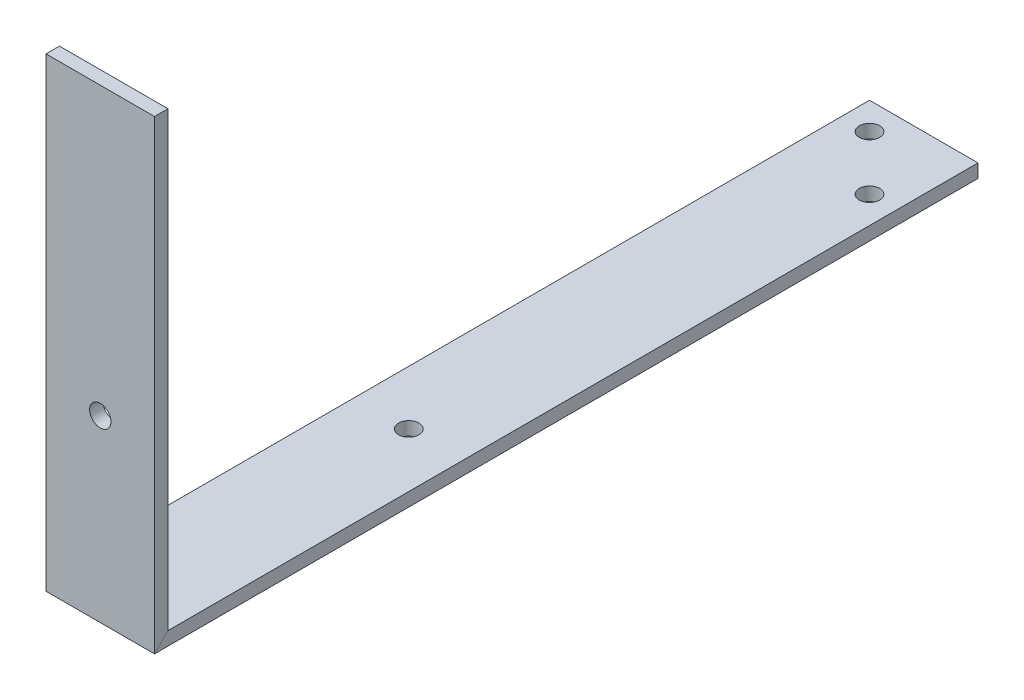
SolidWorks part; units mm, degrees
ref_plane "Alzado" through (0, 0, 0) normal (0, 0, 1) x (1, 0, 0)
ref_plane "Planta" through (0, 0, 0) normal (0, 1, 0) x (1, 0, 0)
ref_plane "Vista lateral" through (0, 0, 0) normal (1, 0, 0) x (0, 0, -1)
sketch "Croquis2" plane through (0, 0, 0) normal (0, 1, 0) x (1, 0, 0)
  line L1 (-25.4, 3.155) -> (25.4, 3.155)
  line L2 (-25.4, 3.155) -> (-25.4, -3.155)
  line L3 (-25.4, -3.155) -> (25.4, -3.155)
  line L4 (25.4, 3.155) -> (25.4, -3.155)
  line L5 (-25.4, 3.155) -> (25.4, -3.155) construction
  line L6 (-25.4, -3.155) -> (25.4, 3.155) construction
  line L7 (184.6, 3.155) -> (235.4, 3.155)
  line L8 (184.6, 3.155) -> (184.6, -3.155)
  line L9 (184.6, -3.155) -> (235.4, -3.155)
  line L10 (235.4, 3.155) -> (235.4, -3.155)
  line L11 (184.6, 3.155) -> (235.4, -3.155) construction
  line L12 (184.6, -3.155) -> (235.4, 3.155) construction
  point P0 (0, 0)
  point P6 (210, 0)
  dimension "D1" = 50.8
  dimension "D2" = 6.31
  dimension "D3" = 210
  dimension "D4" = 50.8
  dimension "D5" = 6.31
sketch3d "Croquis3D1"
  line L0 (0, 0, 0) -> (0, -567.24, 0)
  line L1 (0, -567.24, 0) -> (0, -567.24, 336.2)
  line L2 (0, -567.24, 336.2) -> (1786.7, -567.24, 336.2)
  line L3 (1786.7, -567.24, 336.2) -> (1786.7, -567.24, 693.16)
  line L4 (-25.4, 0, 0) -> (-25.4, -383.9185, 0) construction
  line L5 (-25.4, 0, -3.155) -> (-25.4, 0, 3.155) construction
  line L6 (-25.4, -383.9185, 0) -> (-25.4, -383.9185, 653.2834) construction
  line L7 (1786.7, -567.24, 693.16) -> (1786.7, -436.23, 693.16)
  line L8 (1786.7, -436.23, 693.16) -> (1786.7, -436.23, 1487.1629)
  dimension "D1" = 567.24
  dimension "D2" = 336.2
  dimension "D3" = 1786.7
  dimension "D4" = 356.96
  dimension "D5" = 131.01
  dimension "D6" = 794.0029
sweep "Barrer1" add profiles "Croquis2" path "Croquis3D1"
sketch "Croquis3" plane through (0, 0, -3.155) normal (0, 0, -1) x (-1, 0, 0)
  line L0 (-235.4, 0) -> (-235.4, -6.31)
  line L1 (-235.4, 0) -> (-235.4, -570.395) construction
  line L2 (-235.4, -6.31) -> (-184.6, -6.31)
  line L3 (-184.6, 0) -> (-184.6, -570.395) construction
  line L4 (-184.6, -6.31) -> (-184.6, 0)
  line L5 (-184.6, 0) -> (-235.4, 0)
  line L7 (-25.4, 0) -> (-25.4, -6.31)
  line L8 (-25.4, 0) -> (-25.4, -570.395) construction
  line L9 (-25.4, -6.31) -> (25.4, -6.31)
  line L10 (25.4, 0) -> (25.4, -570.395) construction
  line L11 (25.4, -6.31) -> (25.4, 0)
  line L12 (-25.4, 0) -> (25.4, 0) construction
  line L13 (25.4, 0) -> (-25.4, 0)
  dimension "D1" = 6.31
  dimension "D2" = 6.31
sketch3d "Croquis3D2"
  line L0 (25.4, -3.155, -3.155) -> (-0.201, -3.155, -3.155) construction
  line L1 (25.4, 0, -3.155) -> (25.4, -6.31, -3.155) construction
  line L2 (-0.201, -3.155, -3.155) -> (-0.201, -5.2746, -3.155) construction
  line L3 (-0.201, -3.155, -3.155) -> (-0.201, -3.155, -207.155)
  line L4 (-0.201, -3.155, -207.155) -> (-0.201, -53.155, -207.155)
  dimension "D1" = 204
  dimension "D2" = 50
sweep "Barrer4" add profiles "Croquis3" path "Croquis3D2"
sketch "Croquis4" plane through (0, 0, -210.31) normal (0, 0, -1) x (-1, 0, 0)
  line L0 (-184.6, 0) -> (-184.6, -53.155)
  line L1 (-184.6, -53.155) -> (-124.6, -53.155)
  line L2 (-124.6, -53.155) -> (-124.6, 0)
  line L3 (-124.6, 0) -> (-184.6, 0)
  dimension "D1" = 60
extrude "Saliente-Extruir1" add sketch "Croquis4" against normal blind 6.31
sketch "Croquis5" plane through (0, 0, -204) normal (0, 0, 1) x (1, 0, 0)
  line L0 (184.6, -6.31) -> (124.6, -6.31)
  line L1 (124.6, -53.155) -> (124.6, 0) construction
  line L2 (124.6, -6.31) -> (124.6, 0)
  line L3 (124.6, 0) -> (184.6, 0)
  line L4 (184.6, 0) -> (184.6, -6.31)
extrude "Cortar-Extruir1" cut sketch "Croquis5" against normal blind 6.31
sketch "Croquis6" plane through (0, -433.075, 0) normal (0, 1, 0) x (1, 0, 0)
  circle A0 centre (1285.7, -1260.295) radius 4.75
  circle A1 centre (1495.7, -1260.295) radius 4.75
sketch "Croquis7" plane through (0, 0, 0) normal (0, 1, 0) x (1, 0, 0)
  line L0 (1761.3, -361.6) -> (2022.1, -361.6)
  line L1 (2022.1, -100.8) -> (2022.1, -690.005) construction
  line L2 (2022.1, -361.6) -> (2022.1, 278.6006)
  line L3 (2022.1, 278.6006) -> (-188.1159, 278.6006)
  line L4 (-188.1159, 278.6006) -> (-188.1159, -361.6)
  line L5 (-188.1159, -361.6) -> (1761.3, -361.6)
extrude "Cortar-Extruir2" cut sketch "Croquis7" against normal blind 634
sketch "Croquis8" plane through (0, 0, 361.6) normal (0, 0, -1) x (-1, 0, 0)
  line L0 (-1812.1, -564.085) -> (-1761.3, -564.085)
  line L1 (-1761.3, -564.085) -> (-1761.3, -570.395)
  line L2 (-1761.3, -570.395) -> (-1812.1, -570.395)
  line L3 (-1812.1, -570.395) -> (-1812.1, -564.085)
extrude "Saliente-Extruir2" add sketch "Croquis8" along normal blind 63.5
sketch "Croquis9" plane through (0, -433.075, 0) normal (0, 1, 0) x (1, 0, 0)
  line L0 (1786.7, -1487.1629) -> (1996.7, -1487.1629) construction
  line L1 (1761.3, -1487.1629) -> (1812.1, -1487.1629) construction
  line L2 (1971.3, -1487.1629) -> (2022.1, -1487.1629) construction
  line L3 (1996.7, -1487.1629) -> (1996.7, -1454.1629) construction
  line L4 (1996.7, -1454.1629) -> (1996.7, -1234.1629) construction
  line L5 (1786.7, -1487.1629) -> (1786.7, -1454.1629) construction
  line L6 (1786.7, -1454.1629) -> (1786.7, -1234.1629) construction
  circle A0 centre (1786.7, -1454.1629) radius 5
  circle A1 centre (1786.7, -1234.1629) radius 5
  circle A2 centre (1996.7, -1234.1629) radius 5
  circle A3 centre (1996.7, -1454.1629) radius 5
  dimension "D3" = 10
  dimension "D4" = 10
  dimension "D5" = 10
  dimension "D6" = 10
  dimension "D1" = 33
  dimension "D2" = 220
extrude "Cortar-Extruir3" cut sketch "Croquis9" against normal blind 10
sketch "Croquis10" plane through (2022.1, 0, 0) normal (1, 0, 0) x (0, 0, -1)
  line L0 (-696.315, -439.385) -> (-696.315, -433.075)
  line L1 (-690.005, -433.075) -> (-1487.1629, -433.075) construction
  line L2 (-696.315, -433.075) -> (-1487.1629, -433.075)
  line L3 (-1487.1629, -433.075) -> (-1487.1629, -439.385)
  line L4 (-1487.1629, -439.385) -> (-696.315, -439.385)
extrude "Cortar-Extruir4" cut sketch "Croquis10" against normal blind 286
sketch "Croquis11" plane through (0, -433.075, 0) normal (0, 1, 0) x (1, 0, 0)
  line L0 (2022.1, -696.315) -> (2022.1, -690.005)
  line L1 (2022.1, -690.005) -> (1761.3, -690.005)
  line L2 (1761.3, -690.005) -> (1761.3, -696.315)
  line L3 (1761.3, -696.315) -> (2022.1, -696.315)
  line L4 (2022.1, -696.315) -> (2028.4123, -762.8726)
  line M1 (1971.3, -690.005) -> (1971.3, -696.315)
  line M2 (1971.3, -696.315) -> (2022.1, -696.315)
  line M3 (2022.1, -696.315) -> (2022.1, -690.005)
  line M4 (2022.1, -690.005) -> (1971.3, -690.005)
extrude "Cortar-Extruir5" cut sketch "Croquis11" against normal blind 13.11 contours M4 M1 M2 M3 | L2 L3 L1 M1
sketch "Croquis12" plane through (0, 0, 361.6) normal (0, 0, -1) x (-1, 0, 0)
  line L0 (-2022.1, -564.085) -> (-2022.1, -570.395)
  line L1 (-2022.1, -570.395) -> (-1971.3, -570.395)
  line L2 (-1971.3, -570.395) -> (-1971.3, -564.085)
  line L3 (-1971.3, -564.085) -> (-2022.1, -564.085)
extrude "Saliente-Extruir3" add sketch "Croquis12" along normal blind 6.35
sketch "Croquis13" plane through (0, -564.085, 0) normal (0, 1, 0) x (1, 0, 0)
  line L0 (1812.1, -298.1) -> (1812.1, -304.45)
  line L1 (1812.1, -298.1) -> (1812.1, -690.005) construction
  line L2 (1812.1, -304.45) -> (1761.3, -304.45)
  line L3 (1761.3, -298.1) -> (1761.3, -690.005) construction
  line L4 (1761.3, -304.45) -> (1761.3, -298.1)
  line L5 (1761.3, -298.1) -> (1812.1, -298.1)
  dimension "D1" = 6.35
extrude "Cortar-Extruir6" cut sketch "Croquis13" against normal blind 6.35
sketch "Croquis14" plane through (0, -446.185, 0) normal (0, 1, 0) x (1, 0, 0)
  line L0 (1761.3, -696.315) -> (1761.3, -690.005)
  line L1 (1761.3, -690.005) -> (2022.1, -690.005)
  line L2 (2022.1, -690.005) -> (2022.1, -696.315)
  line L3 (2022.1, -696.315) -> (1761.3, -696.315)
extrude "Cortar-Extruir7" cut sketch "Croquis14" against normal blind 6.31
sketch "Croquis15" plane through (0, 0, 304.45) normal (0, 0, -1) x (-1, 0, 0)
  line L0 (-1812.1, -564.085) -> (-1812.1, -570.395)
  line L1 (-1812.1, -570.395) -> (-1761.3, -570.395)
  line L2 (-1761.3, -570.395) -> (-1761.3, -564.085)
  line L3 (-1761.3, -564.085) -> (-1812.1, -564.085)
extrude "Cortar-Extruir8" cut sketch "Croquis15" against normal blind 6.31
sketch "Croquis16" plane through (0, -452.495, 0) normal (0, 1, 0) x (1, 0, 0)
  line L1 (2033.1978, -330.6694) -> (1954.4214, -330.6694)
  line L2 (2033.1978, -330.6694) -> (2033.1978, -785.1486)
  line L3 (2033.1978, -785.1486) -> (1954.4214, -785.1486)
  line L4 (1954.4214, -330.6694) -> (1954.4214, -785.1486)
  line L5 (2033.1978, -330.6694) -> (1954.4214, -785.1486) construction
  line L6 (2033.1978, -785.1486) -> (1954.4214, -330.6694) construction
  point P0 (1993.8096, -557.909)
extrude "Cortar-Extruir9" cut sketch "Croquis16" against normal blind 128
sketch "Croquis22" plane through (0, -564.085, 0) normal (0, 1, 0) x (1, 0, 0)
  line L0 (1786.7, -690.005) -> (1786.7, -551.855) construction
  line L1 (1812.1, -690.005) -> (1761.3, -690.005) construction
  line L2 (1786.7, -336.2) -> (1786.7, -693.16) construction
  circle A0 centre (1786.7, -551.855) radius 4.7625
  dimension "D2" = 9.525
  dimension "D1" = 138.15
extrude "Cortar-Extruir15" cut sketch "Croquis22" against normal blind 33
sketch "Croquis24" plane through (0, 0, 690.005) normal (0, 0, -1) x (-1, 0, 0)
  circle A0 centre (-1786.7, -486.4987) radius 5
extrude "Cortar-Extruir18" cut sketch "Croquis24" against normal blind 33
sketch "Croquis25" plane through (0, -570.395, 0) normal (0, -1, 0) x (-1, 0, 0)
  circle A0 centre (-1799.4, -348.8622) radius 4.7625
  circle A1 centre (-1774, -323.4622) radius 4.7625
extrude "Cortar-Extruir19" cut sketch "Croquis25" against normal blind 50
sketch "Croquis26" plane through (0, -452.495, 0) normal (0, 1, 0) x (1, 0, 0)
  line L0 (1761.3, -696.315) -> (1761.3, -690.005)
  line L1 (1761.3, -690.005) -> (1812.1, -690.005)
  line L2 (1812.1, -690.005) -> (1812.1, -696.315)
  line L3 (1812.1, -696.315) -> (1761.3, -696.315)
extrude "Saliente-Extruir4" add sketch "Croquis26" along normal blind 100
